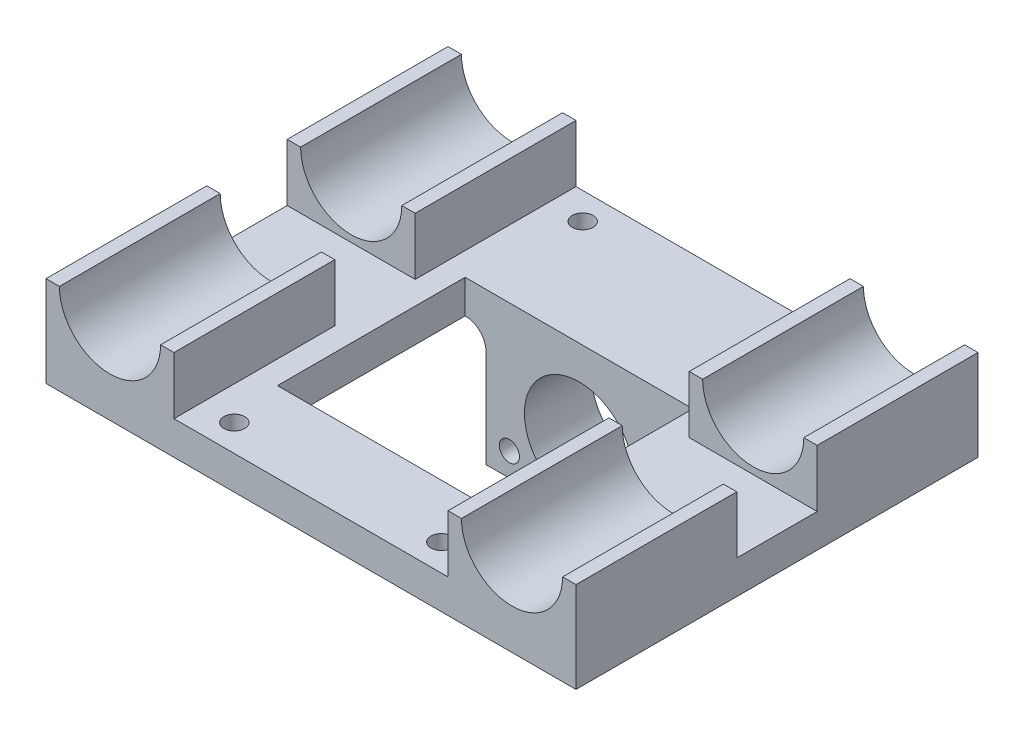
SolidWorks part; units mm, degrees
ref_plane "Front Plane" through (0, 0, 0) normal (0, 0, 1) x (1, 0, 0)
ref_plane "Top Plane" through (0, 0, 0) normal (0, 1, 0) x (1, 0, 0)
ref_plane "Right Plane" through (0, 0, 0) normal (1, 0, 0) x (0, 0, -1)
sketch "Sketch1" plane through (0, 0, 0) normal (0, 1, 0) x (1, 0, 0)
  line L1 (-39.55, 30) -> (39.55, 30)
  line L2 (-39.55, 30) -> (-39.55, -30)
  line L3 (-39.55, -30) -> (39.55, -30)
  line L4 (39.55, 30) -> (39.55, -30)
  dimension "D1" = 60
  dimension "D2" = 79.1
  dimension "D3" = 39.55
  dimension "D4" = 30
extrude "Boss-Extrude1" add sketch "Sketch1" along normal blind 5
sketch "Sketch2" plane through (0, 0, 30) normal (0, 0, 1) x (1, 0, 0)
  line L0 (-39.55, 5) -> (39.55, 5) construction
  line L1 (-39.55, 5) -> (-20.45, 5)
  line L2 (-39.55, 5) -> (-39.55, 13.55)
  line L3 (-39.55, 13.55) -> (-20.45, 13.55)
  line L4 (-20.45, 5) -> (-20.45, 13.55)
  circle A0 centre (-30, 13.55) radius 7.55
  line M3 (39.55, 5) -> (-39.55, 5)
  dimension "D3" = 15.1
  dimension "D1" = 19.1
  dimension "D2" = 8.55
  dimension "D4" = 30
extrude "Boss-Extrude2" add sketch "Sketch2" against normal blind 24 contours A0 L3 L2 L4 M3
mirror "Mirror1" about plane through (0, 0, 0) normal (0, 0, 1) of "Boss-Extrude2"
mirror "Mirror2" about plane through (0, 0, 0) normal (1, 0, 0) of "Mirror1", "Boss-Extrude2"
ref_plane "Plane1" through (-30, 0, 0) normal (-1, 0, 0) x (0, 0, 1)
ref_plane "Plane2" through (-22.275, 22.275, 0) normal (-0.7071, 0.7071, 0) x (0.7071, 0.7071, 0)
ref_plane "Plane3" through (0, 0, -10) normal (0, 0, -1) x (-1, 0, 0)
sketch "Sketch3" plane through (-22.275, 22.275, 0) normal (-0.7071, 0.7071, 0) x (0.7071, 0.7071, 0)
  line L0 (-27.9661, -30) -> (-18.3848, -30) construction
  line L2 (-24.4305, -6) -> (-24.4305, 6) construction
  circle A0 centre (-27.9305, -18) radius 1.75
  dimension "D1" = 3.5
  dimension "D2" = 12
  dimension "D3" = 3.5
sketch "Sketch10" plane through (0, 5, 0) normal (0, 1, 0) x (1, 0, 0)
  line L0 (-20.45, 6) -> (-20.45, 30) construction
  line L1 (20.45, 30) -> (-20.45, 30) construction
  line L2 (20.45, 6) -> (20.45, 30) construction
  line L3 (20.45, -6) -> (20.45, -30) construction
  line L4 (-20.45, -30) -> (20.45, -30) construction
  line L5 (-20.45, -6) -> (-20.45, -30) construction
  circle A0 centre (-15.45, -26) radius 1.55
  circle A1 centre (-15.45, 26) radius 1.55
  circle A2 centre (15.45, 26) radius 1.55
  circle A3 centre (15.45, -26) radius 1.55
  dimension "D1" = 3.1
  dimension "D2" = 5
  dimension "D3" = 4
  dimension "D4" = 4
  dimension "D5" = 5
  dimension "D6" = 5
  dimension "D7" = 4
  dimension "D8" = 5
  dimension "D9" = 4
extrude "Cut-Extrude7" cut sketch "Sketch10" against normal blind 8
sketch "Sketch11" plane through (0, 0, 0) normal (0, -1, 0) x (1, 0, 0)
  circle A0 centre (-15.45, 26) radius 3
  circle A1 centre (15.45, 26) radius 3
  circle A2 centre (15.45, -26) radius 3
  circle A3 centre (-15.45, -26) radius 3
  dimension "D1" = 6
extrude "Cut-Extrude8" cut sketch "Sketch11" against normal blind 1
sketch "Sketch12" plane through (0, 0, -10) normal (0, 0, 1) x (1, 0, 0)
  line L1 (-39.55, 0) -> (39.55, 0) construction
  line L2 (10.45, 0) -> (10.45, -8.153)
  line L3 (20.45, 5) -> (20.45, 13.55) construction
  line L4 (-10.45, 0) -> (10.45, 0)
  line L5 (-13.8923, 0) -> (13.8923, 0)
  line L6 (-13.8923, 0) -> (-13.8923, -17.653)
  line L7 (-13.8923, -17.653) -> (13.8923, -17.653)
  line L8 (13.8923, 0) -> (13.8923, -17.653)
  circle A0 centre (0, -8.153) radius 8.15
  circle A2 centre (0, -8.153) radius 15
  circle A3 centre (0, -8.153) radius 12
  circle A4 centre (0, 3.847) radius 1.5
  circle A5 centre (10.3923, -14.153) radius 1.5
  circle A6 centre (-10.3923, -14.153) radius 1.5
  point P22 (0, -8.153)
  dimension "D1" = 16.3
  dimension "D2" = 8.153
  dimension "D4" = 30
  dimension "D5" = 24
  dimension "D6" = 3
  dimension "D7" = 3.5
  dimension "D3" = 10
  dimension "D8" = 3.5
  dimension "D9" = 3.5
extrude "Boss-Extrude5" add sketch "Sketch12" against normal blind 10
sketch "Sketch13" plane through (0, 0, 0) normal (0, -1, 0) x (1, 0, 0)
  line L1 (-17, 18) -> (17, 18)
  line L2 (-17, 18) -> (-17, -10)
  line L3 (-17, -10) -> (17, -10)
  line L4 (17, 18) -> (17, -10)
  line L5 (-17, 18) -> (17, -10) construction
  line L6 (-17, -10) -> (17, 18) construction
  point P0 (0, 4)
  dimension "D1" = 34
  dimension "D2" = 28
extrude "Cut-Extrude9" cut sketch "Sketch13" against normal blind 10
fillet "Fillet2" radius 3 2 edges at (13.8923, 0, -15) (-13.8923, 0, -15)
ref_plane "Plane4" through (-15.7727, -15.7727, 0) normal (-0.7071, -0.7071, 0) x (-0.7071, 0.7071, 0)
sketch "Sketch15" plane through (-15.7727, -15.7727, 0) normal (-0.7071, -0.7071, 0) x (-0.7071, 0.7071, 0)
  line L0 (-2.6592, 20) -> (-2.6592, 10) construction
  line L1 (-5.6592, 15.3) -> (0.3408, 15.3)
  line L2 (-5.6592, 15.3) -> (-5.6592, 12.5)
  line L3 (-5.6592, 12.5) -> (0.3408, 12.5)
  line L4 (0.3408, 15.3) -> (0.3408, 12.5)
  line L5 (-5.6592, 15.3) -> (0.3408, 12.5) construction
  line L6 (-5.6592, 12.5) -> (0.3408, 15.3) construction
  line L7 (7.4525, 10) -> (-7.4525, 10) construction
  point P0 (-2.6592, 13.9)
  dimension "D1" = 6
  dimension "D2" = 2.8
  dimension "D3" = 2.5
extrude "Cut-Extrude12" cut sketch "Sketch15" against normal blind 8.2
mirror "Mirror3" about plane through (0, 0, 0) normal (1, 0, 0) of "Cut-Extrude12"
sketch "Sketch16" plane through (0, 0, 30) normal (0, 0, 1) x (1, 0, 0)
  line L8 (-13.8923, -17.653) -> (13.8923, -17.653)
  line L9 (13.8923, -17.653) -> (13.8923, -3)
  line L10 (16.8923, 0) -> (17, 0)
  line L11 (17, 0) -> (17, 5)
  line L12 (17, 5) -> (-17, 5)
  line L13 (-17, 5) -> (-17, 0)
  line L14 (-17, 0) -> (-16.8923, 0)
  line L15 (-13.8923, -3) -> (-13.8923, -17.653)
  line L16 (-13.8923, -17.653) -> (13.8923, -17.653)
  line L17 (13.8923, -17.653) -> (13.8923, -3)
  line L18 (16.8923, 0) -> (17, 0)
  line L19 (17, 0) -> (17, 5)
  line L20 (17, 5) -> (-17, 5)
  line L21 (-17, 5) -> (-17, 0)
  line L22 (-17, 0) -> (-16.8923, 0)
  line L23 (-13.8923, -3) -> (-13.8923, -17.653)
  circle A1 centre (0, -8.153) radius 8.15 construction
  circle A2 centre (0, -8.153) radius 8.15
  arc A5 (16.8923, 0) -> (13.8923, -3) centre (16.8923, -3) ccw
  arc A6 (-13.8923, -3) -> (-16.8923, 0) centre (-16.8923, -3) ccw
  arc A7 (16.8923, 0) -> (13.8923, -3) centre (16.8923, -3) ccw
  arc A8 (-13.8923, -3) -> (-16.8923, 0) centre (-16.8923, -3) ccw
  dimension "D1" = 0
